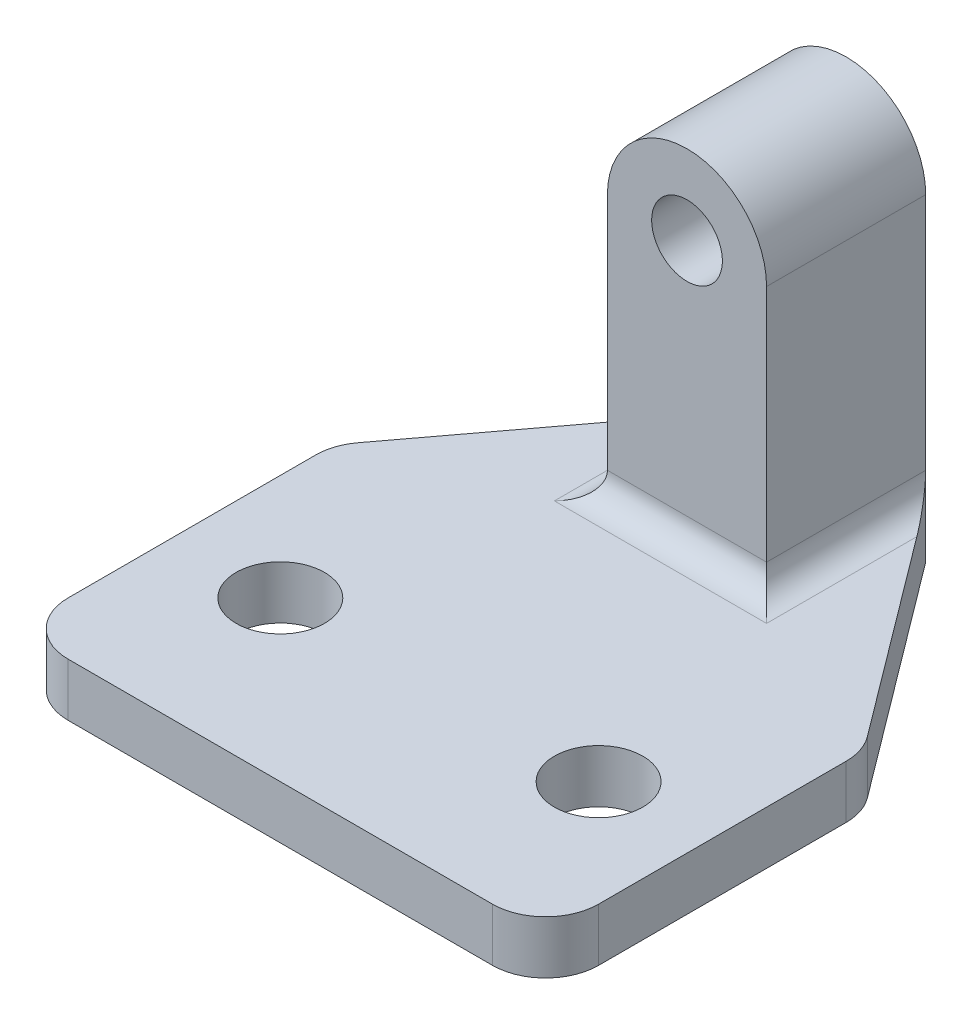
SolidWorks part; units mm, degrees
ref_plane "Front Plane" through (0, 0, 0) normal (0, 0, 1) x (1, 0, 0)
ref_plane "Top Plane" through (0, 0, 0) normal (0, 1, 0) x (1, 0, 0)
ref_plane "Right Plane" through (0, 0, 0) normal (1, 0, 0) x (0, 0, -1)
sketch "Sketch1" plane through (0, 0, 0) normal (0, 1, 0) x (1, 0, 0)
  line L0 (-15, 9) -> (-4.5, 23)
  line L1 (15, -9) -> (-15, -9)
  line L2 (15, -9) -> (15, 9)
  line L4 (-15, -9) -> (-15, 9)
  line L5 (15, -9) -> (-15, 9) construction
  line L6 (15, 9) -> (-15, -9) construction
  line L7 (-4.5, 23) -> (4.5, 23)
  line L8 (4.5, 23) -> (15, 9)
  point P0 (0, 0)
  point P7 (0, 23)
  dimension "D1" = 30
  dimension "D2" = 18
  dimension "D3" = 32
  dimension "D4" = 4.5
extrude "Boss-Extrude1" add sketch "Sketch1" along normal blind 3
sketch "Sketch2" plane through (0, 0, -23) normal (0, 0, -1) x (-1, 0, 0)
  line L1 (-4.5, 3) -> (4.5, 3) construction
  line L2 (-4.5, 3) -> (-4.5, 18)
  line L3 (4.5, 3) -> (4.5, 18)
  line L4 (-4.5, 3) -> (4.5, 3)
  arc A0 (4.5, 18) -> (-4.5, 18) centre (0, 18) ccw
  circle A1 centre (0, 18) radius 2
  dimension "D1" = 9
  dimension "D3" = 4
  dimension "D2" = 15
extrude "Boss-Extrude2" add sketch "Sketch2" against normal blind 9
fillet "Fillet1" radius 1.5 3 edges at (-4.5, 3, -18.5) (4.5, 3, -18.5) (0, 3, -14)
fillet "Fillet2" radius 3 4 edges at (-15, 1.5, -9) (15, 1.5, -9) (15, 1.5, 9) (-15, 1.5, 9)
sketch "Sketch3" plane through (0, 3, 0) normal (0, 1, 0) x (1, 0, 0)
  line L0 (0, 0) -> (0, -9) construction
  line L1 (-12, -9) -> (12, -9) construction
  line L2 (-15, 8) -> (-15, -6) construction
  circle A0 centre (-9, 0) radius 2.5
  circle A1 centre (9, 0) radius 2.5
  dimension "D1" = 5
  dimension "D2" = 9
  dimension "D3" = 6
extrude "Cut-Extrude1" cut sketch "Sketch3" against normal through all
